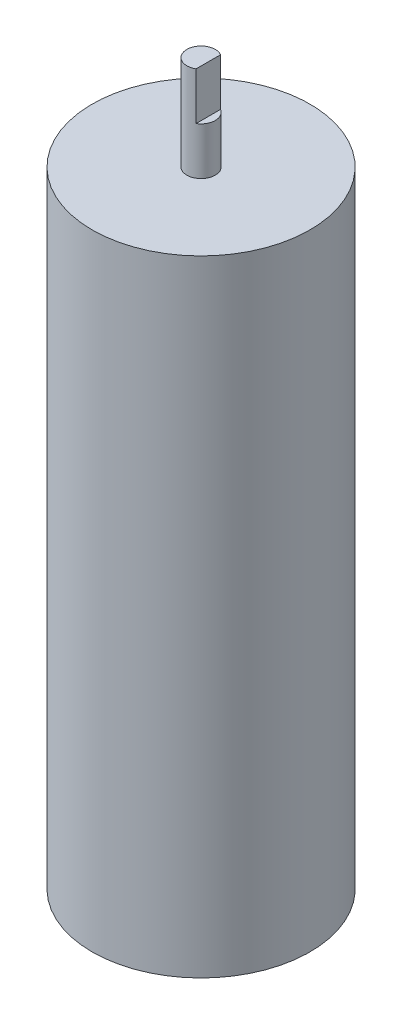
SolidWorks part; units mm, degrees
ref_plane "Front Plane" through (0, 0, 0) normal (0, 0, 1) x (1, 0, 0)
ref_plane "Top Plane" through (0, 0, 0) normal (0, 1, 0) x (1, 0, 0)
ref_plane "Right Plane" through (0, 0, 0) normal (1, 0, 0) x (0, 0, -1)
sketch "Sketch1" plane through (0, 0, 0) normal (0, 1, 0) x (1, 0, 0)
  circle A0 centre (0, 0) radius 11.5
  dimension "D1" = 23
extrude "Boss-Extrude1" add sketch "Sketch1" along normal blind 66
sketch "Sketch2" plane through (0, 66, 0) normal (0, 1, 0) x (1, 0, 0)
  circle A0 centre (0, 0) radius 1.5
  dimension "D1" = 3
extrude "Boss-Extrude2" add sketch "Sketch2" along normal blind 10
sketch "Sketch3" plane through (0, 66, 0) normal (0, 1, 0) x (1, 0, 0)
  circle A0 centre (0, 0) radius 13.5
  dimension "D1" = 27
sketch "Sketch4" plane through (0, 0, 0) normal (0, -1, 0) x (1, 0, 0)
  circle A0 centre (0, 0) radius 1.5
  dimension "D1" = 3
extrude "Boss-Extrude4" add sketch "Sketch4" along normal blind 6
fillet "Fillet1" radius 0.5 1 edges at (0, -6, -1.5)
sketch "Sketch5" plane through (0, 76, 0) normal (0, 1, 0) x (1, 0, 0)
  line L0 (0.7656, 1.2899) -> (0.7656, -1.2899) construction
  line L1 (0.7656, 1.2899) -> (0.7656, -1.2899)
  arc A0 (0.7656, -1.2899) -> (0.7656, 1.2899) centre (0, 0) ccw
extrude "Cut-Extrude1" cut sketch "Sketch5" against normal blind 5
